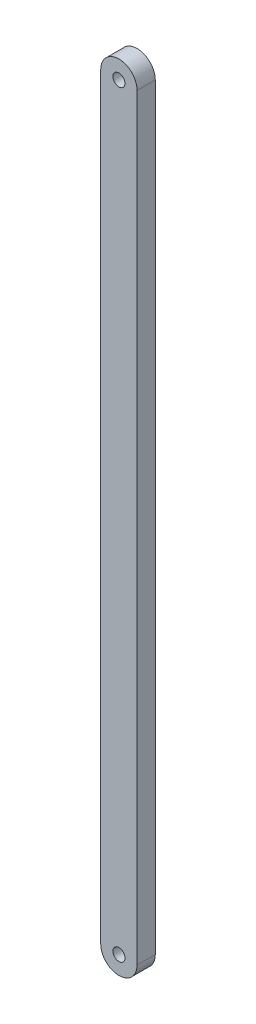
SolidWorks part; units mm, degrees
ref_plane "Front Plane" through (0, 0, 0) normal (0, 0, 1) x (1, 0, 0)
ref_plane "Top Plane" through (0, 0, 0) normal (0, 1, 0) x (1, 0, 0)
ref_plane "Right Plane" through (0, 0, 0) normal (1, 0, 0) x (0, 0, -1)
sketch "Sketch1" plane through (0, 0, 0) normal (0, 0, 1) x (1, 0, 0)
  line L0 (0, 125) -> (0, 0.9719) construction
  line L1 (0, 125) -> (-3, 125) construction
  line L2 (-3, 125) -> (-3, 0)
  line L3 (3, 0) -> (3, 125)
  arc A0 (3, 125) -> (-3, 125) centre (0, 125) ccw
  arc A1 (-3, 0) -> (3, 0) centre (0, 0) ccw
  dimension "D4" = 3
  dimension "D3" = 3
  dimension "D1" = 125
  dimension "D2" = 125
extrude "Boss-Extrude1" add sketch "Sketch1" along normal blind 3
sketch "Sketch2" plane through (0, 0, 3) normal (0, 0, 1) x (1, 0, 0)
  circle A0 centre (0, 125) radius 1
  circle A1 centre (0, 0) radius 1
  dimension "D1" = 2
  dimension "D2" = 2
extrude "Cut-Extrude1" cut sketch "Sketch2" against normal blind 3
